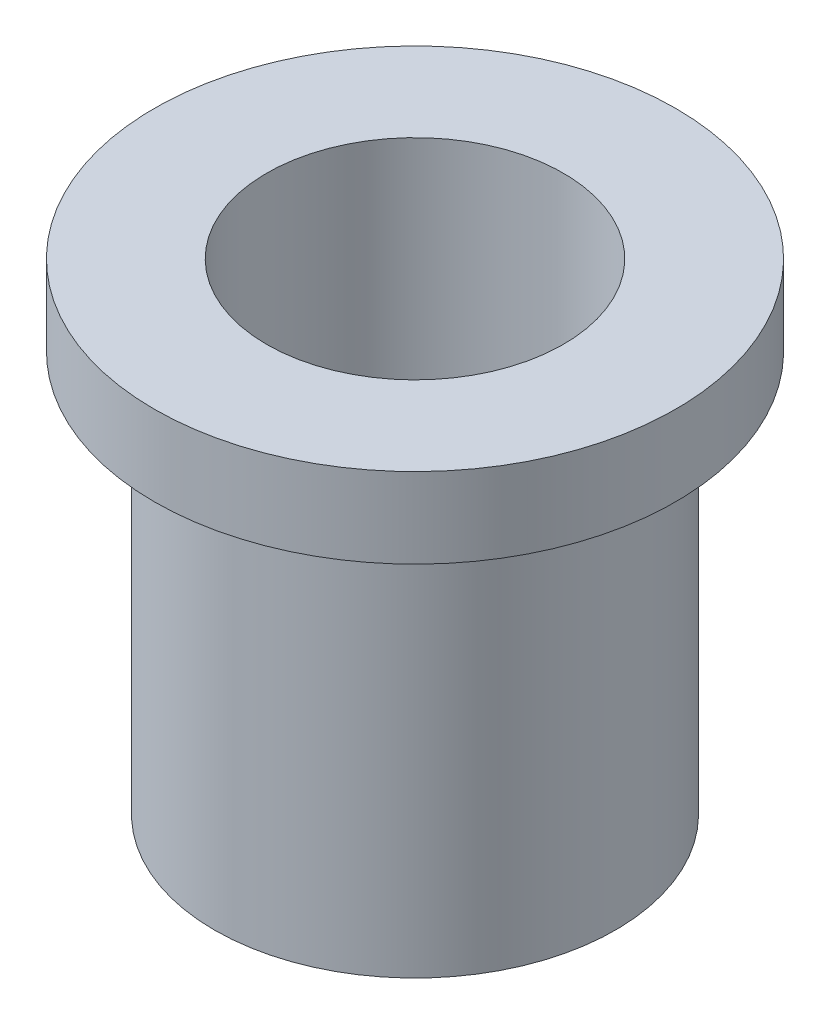
SolidWorks part; units mm, degrees
material "Delrin 2700 NC010, Low Viscosity Acetal Copolymer (SS)"
ref_plane "Front Plane" through (0, 0, 0) normal (0, 0, 1) x (1, 0, 0)
ref_plane "Top Plane" through (0, 0, 0) normal (0, 1, 0) x (1, 0, 0)
ref_plane "Right Plane" through (0, 0, 0) normal (1, 0, 0) x (0, 0, -1)
sketch "Sketch2" plane through (0, 0, 0) normal (0, 1, 0) x (1, 0, 0)
  circle A0 centre (0, 0) radius 3.175
  circle A1 centre (0, 0) radius 2.3495
  dimension "D1" = 6.35
  dimension "D2" = 4.699
extrude "Boss-Extrude1" add sketch "Sketch2" along normal blind 6.35
sketch "Sketch3" plane through (0, 6.35, 0) normal (0, 1, 0) x (1, 0, 0)
  circle A0 centre (0, 0) radius 2.3495
  circle A1 centre (0, 0) radius 4.1275
  circle A2 centre (0, 0) radius 2.3495 construction
  dimension "D1" = 8.255
extrude "Boss-Extrude2" add sketch "Sketch3" along normal blind 1.27
